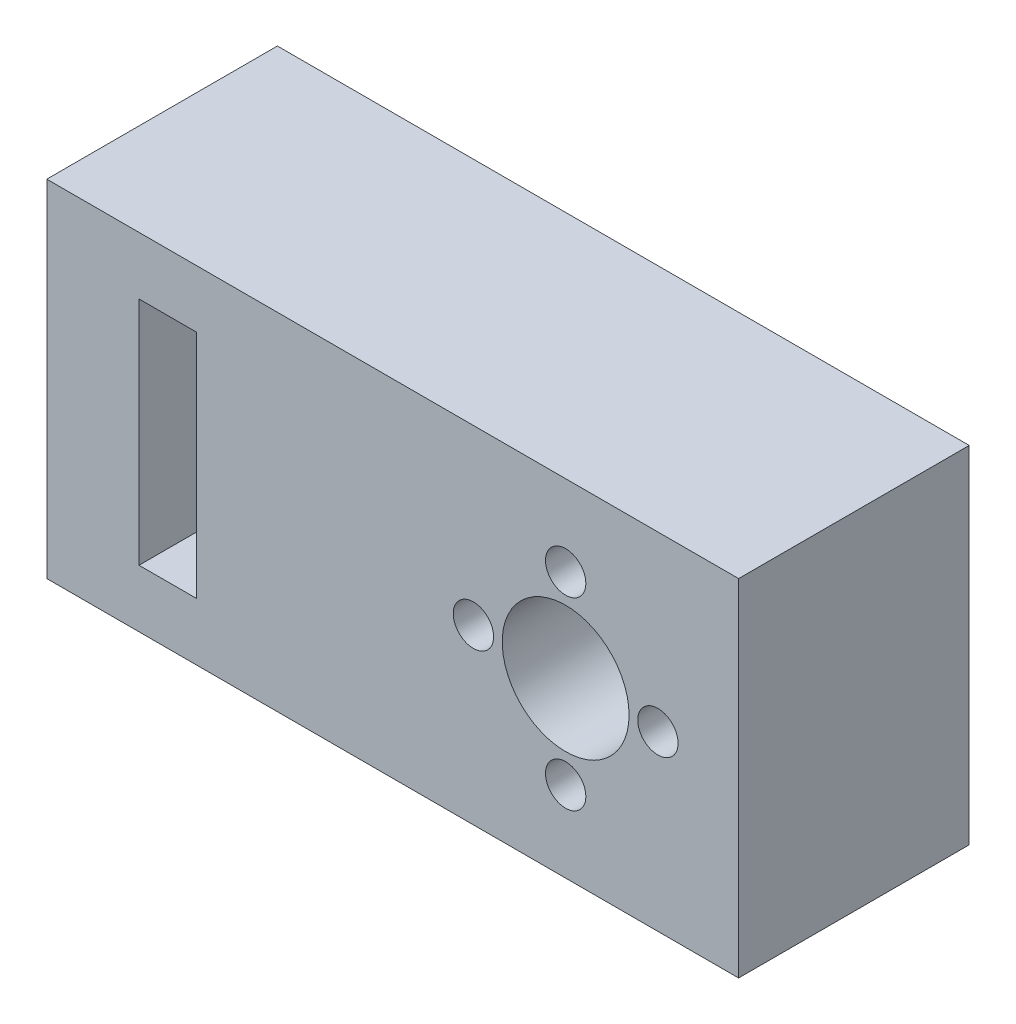
SolidWorks part; units mm, degrees
ref_plane "Front Plane" through (0, 0, 0) normal (0, 0, 1) x (1, 0, 0)
ref_plane "Top Plane" through (0, 0, 0) normal (0, 1, 0) x (1, 0, 0)
ref_plane "Right Plane" through (0, 0, 0) normal (1, 0, 0) x (0, 0, -1)
sketch "Sketch1" plane through (0, 0, 0) normal (0, 0, 1) x (1, 0, 0)
  line L1 (-30, 15) -> (30, 15)
  line L2 (-30, 15) -> (-30, -15)
  line L3 (-30, -15) -> (30, -15)
  line L4 (30, 15) -> (30, -15)
  line L5 (-30, 15) -> (30, -15) construction
  line L6 (-30, -15) -> (30, 15) construction
  line L7 (-22, 10) -> (-17, 10)
  line L8 (-22, 10) -> (-22, -10)
  line L9 (-22, -10) -> (-17, -10)
  line L10 (-17, 10) -> (-17, -10)
  circle A0 centre (15, 0) radius 5.5
  circle A1 centre (15, 8) radius 1.75
  circle A2 centre (23, 0) radius 1.75
  circle A3 centre (15, -8) radius 1.75
  circle A4 centre (7, 0) radius 1.75
  point P0 (0, 0)
  point P24 (15, 0)
  dimension "D1" = 11
  dimension "D9" = 3.5
  dimension "D2" = 45
  dimension "D3" = 60
  dimension "D4" = 30
  dimension "D5" = 8
  dimension "D6" = 5
  dimension "D7" = 20
  dimension "D8" = 5
  dimension "D10" = 8
  dimension "D11" = 4
extrude "Boss-Extrude1" add sketch "Sketch1" along normal mid plane 20
sketch "Sketch2" plane through (-30, 0, 0) normal (-1, 0, 0) x (0, 0, 1)
  circle A0 centre (0, 0) radius 2.5
  dimension "D1" = 5
extrude "Cut-Extrude1" cut sketch "Sketch2" against normal up to surface (8 mm away) up to face at (-22, 0, 0)
